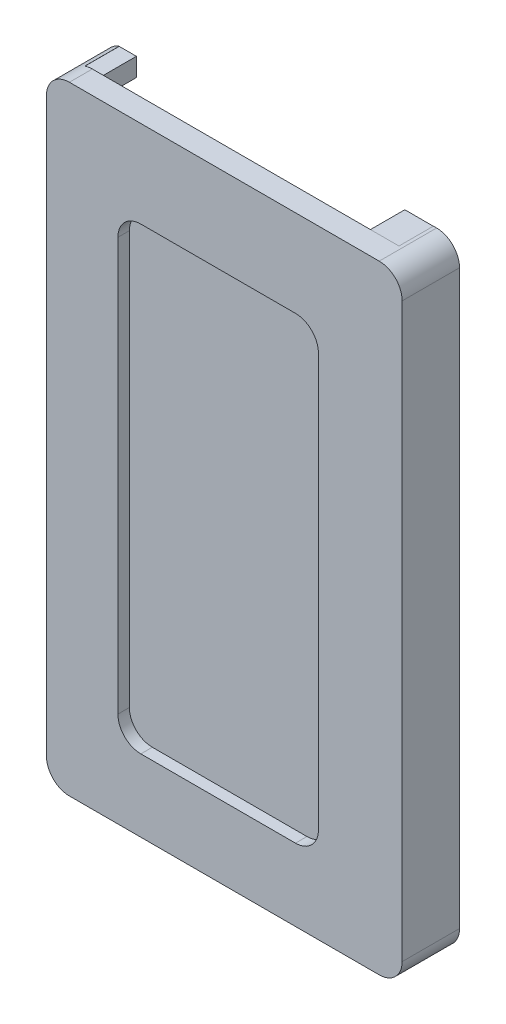
SolidWorks part; units mm, degrees
ref_plane "Front Plane" through (0, 0, 0) normal (0, 0, 1) x (1, 0, 0)
ref_plane "Top Plane" through (0, 0, 0) normal (0, 1, 0) x (1, 0, 0)
ref_plane "Right Plane" through (0, 0, 0) normal (1, 0, 0) x (0, 0, -1)
sketch "草图5" plane through (0, 0, 15) normal (0, 0, 1) x (1, 0, 0)
  line L0 (68.0762, -26.8877) -> (68.0762, -76.7564) construction
  line L1 (37.0762, -24.8877) -> (68.0762, -24.8877)
  line L2 (37.0762, -24.8877) -> (37.0762, -78.7564)
  line L3 (37.0762, -78.7564) -> (68.0762, -78.7564)
  line L4 (68.0762, -24.8877) -> (68.0762, -78.7564)
  line L5 (38.4139, -24.8877) -> (38.4139, -28.6161) construction
  line L6 (38.4139, -26.7519) -> (65.7955, -26.7519)
  line L7 (38.4139, -26.7519) -> (38.4139, -77.1753)
  line L8 (38.4139, -77.1753) -> (65.7955, -77.1753)
  line L9 (65.7955, -26.7519) -> (65.7955, -77.1753)
extrude "凸台-拉伸3" add sketch "草图5" along normal blind 3 contours L2 L1 L4 L3 | L7 L6 L9 L8
sketch "草图8" plane through (0, 0, 15) normal (0, 0, -1) x (-1, 0, 0)
  line L0 (-38.4139, -77.1753) -> (-65.7955, -77.1753) construction
  line L1 (-55.1901, -77.1753) -> (-40.1901, -77.1753)
  line L2 (-55.1901, -77.1753) -> (-55.1901, -78.7564)
  line L3 (-55.1901, -78.7564) -> (-40.1901, -78.7564)
  line L4 (-40.1901, -77.1753) -> (-40.1901, -78.7564)
  line L5 (-37.0762, -78.7564) -> (-68.0762, -78.7564) construction
extrude "切除-拉伸6" cut sketch "草图8" against normal blind 1 contours L2 L1 L4 L3
sketch "草图9" plane through (0, 0, 18) normal (0, 0, 1) x (1, 0, 0)
  line L1 (37.0762, -24.8877) -> (68.0762, -24.8877)
  line L2 (37.0762, -24.8877) -> (37.0762, -78.7564)
  line L3 (37.0762, -78.7564) -> (68.0762, -78.7564)
  line L4 (68.0762, -24.8877) -> (68.0762, -78.7564)
extrude "凸台-拉伸5" add sketch "草图9" along normal blind 2
sketch "草图10" plane through (0, 0, 20) normal (0, 0, 1) x (1, 0, 0)
  line L1 (43.3021, -32.4774) -> (60.7771, -32.4774)
  line L2 (43.3021, -32.4774) -> (43.3021, -72.4639)
  line L3 (43.3021, -72.4639) -> (60.7771, -72.4639)
  line L4 (60.7771, -32.4774) -> (60.7771, -72.4639)
extrude "切除-拉伸7" cut sketch "草图10" against normal blind 1
fillet "圆角1" radius 2 4 edges at (68.0762, -78.7564, 17.5) (37.0762, -78.7564, 17.5) (37.0762, -24.8877, 17.5) (68.0762, -24.8877, 17.5)
fillet "圆角2" radius 2 4 edges at (43.3021, -72.4639, 19.5) (60.7771, -72.4639, 19.5) (60.7771, -32.4774, 19.5) (43.3021, -32.4774, 19.5)
sketch "草图11" plane through (0, -26.7519, 0) normal (0, -1, 0) x (-1, 0, 0)
  line L0 (-65.7955, -18) -> (-65.7955, -15) construction
  line L1 (-38.4139, -15) -> (-65.7955, -15) construction
  line L2 (-38.4139, -18) -> (-65.7955, -18) construction
  line L3 (-38.4139, -18) -> (-38.4139, -15) construction
  line L4 (-65.7955, -18) -> (-65.7955, -15)
  line L5 (-38.4139, -15) -> (-65.7955, -15)
  line L6 (-38.4139, -18) -> (-65.7955, -18)
  line L7 (-38.4139, -18) -> (-38.4139, -15)
extrude "切除-拉伸8" cut sketch "草图11" against normal blind 2
sketch "草图14" plane through (0, 0, 18) normal (0, 0, -1) x (-1, 0, 0)
  line L0 (-65.8048, -24.8943) -> (-63.3048, -24.8943) construction
  line L1 (-65.8048, -24.8943) -> (-63.3048, -24.8943)
  line L2 (-65.8048, -24.8943) -> (-63.3048, -24.8943)
  line L3 (-65.8048, -24.8943) -> (-63.3048, -24.8943)
  line L4 (-65.7955, -77.1753) -> (-38.4139, -77.1753)
  line L5 (-38.4139, -77.1753) -> (-38.4139, -25.0005)
  line L6 (-39.0762, -24.8877) -> (-65.7955, -24.8877)
  line L7 (-65.7955, -24.8877) -> (-65.7955, -77.1753)
  line L9 (-38.4139, -26.6161) -> (-38.4139, -25.0005)
  line L11 (-65.7955, -24.8877) -> (-65.7955, -26.6161)
  line L12 (-38.4139, -25.0096) -> (-39.9139, -25.0096) construction
  line L13 (-39.9139, -25.0096) -> (-39.9139, -26.6161) construction
  line L14 (-38.4139, -26.6161) -> (-39.9139, -26.6161) construction
  line L15 (-65.7955, -26.6161) -> (-63.3048, -26.6161) construction
  line L16 (-63.3048, -24.8943) -> (-63.3048, -26.6161) construction
  line L17 (-38.4139, -25.0096) -> (-39.9139, -25.0096)
  line L18 (-39.9139, -25.0096) -> (-39.9139, -26.6161)
  line L19 (-38.4139, -26.6161) -> (-39.9139, -26.6161)
  line L20 (-65.7955, -26.6161) -> (-63.3048, -26.6161)
  line L21 (-65.8048, -24.8943) -> (-63.3048, -24.8943)
  line L22 (-63.3048, -24.8943) -> (-63.3048, -26.6161)
  arc A1 (-38.4139, -25.0005) -> (-39.0762, -24.8877) centre (-39.0762, -26.8877) ccw
  line M7 (-38.4139, -77.1753) -> (-38.4139, -25.0005)
  line M10 (-65.7955, -24.8877) -> (-65.7955, -77.1753)
  dimension "D1" = 0
extrude "凸台-拉伸6" add sketch "草图14" along normal blind 3 contours L22 L1 L20 M10 | L19 L17 L18 M7
